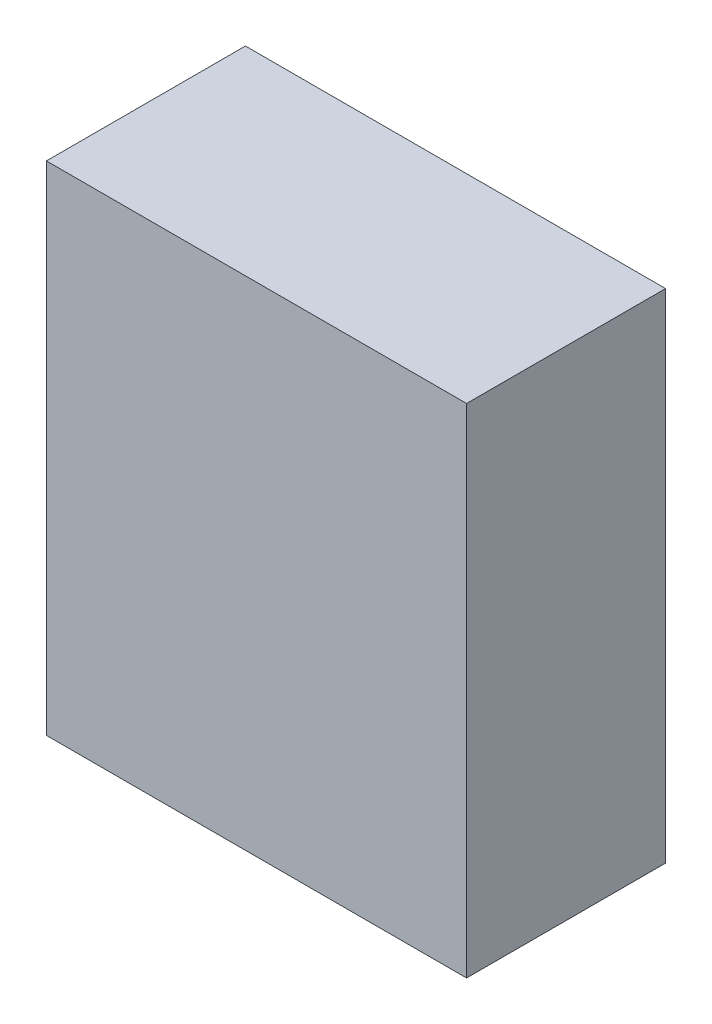
SolidWorks part; units mm, degrees
material "Plain Carbon Steel"
ref_plane "Front Plane" through (0, 0, 0) normal (0, 0, 1) x (1, 0, 0)
ref_plane "Top Plane" through (0, 0, 0) normal (0, 1, 0) x (1, 0, 0)
ref_plane "Right Plane" through (0, 0, 0) normal (1, 0, 0) x (0, 0, -1)
sketch "Sketch1" plane through (0, 0, 0) normal (0, 1, 0) x (1, 0, 0)
  line L1 (0, 0) -> (965.2, 0)
  line L2 (0, 0) -> (0, 457.2)
  line L3 (0, 457.2) -> (965.2, 457.2)
  line L4 (965.2, 0) -> (965.2, 457.2)
  dimension "D1" = 965.2
  dimension "D2" = 457.2
extrude "Extrude1" add sketch "Sketch1" along normal blind 1143
